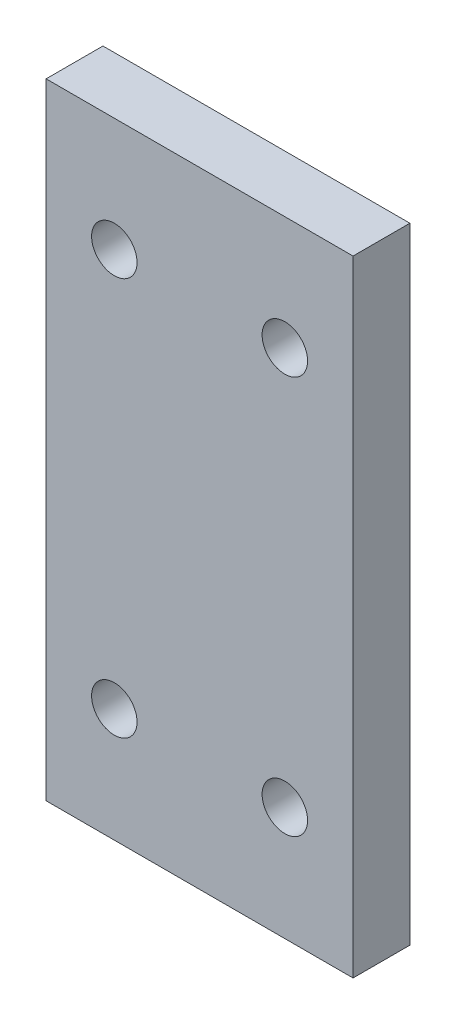
SolidWorks part; units mm, degrees
ref_plane "Front Plane" through (0, 0, 0) normal (0, 0, 1) x (1, 0, 0)
ref_plane "Top Plane" through (0, 0, 0) normal (0, 1, 0) x (1, 0, 0)
ref_plane "Right Plane" through (0, 0, 0) normal (1, 0, 0) x (0, 0, -1)
sketch "Sketch1" plane through (0, 0, 0) normal (0, 0, 1) x (1, 0, 0)
  line L0 (-25, 55) -> (-25, 0) construction
  line L1 (0, 0) -> (-27, 0)
  line L2 (0, 0) -> (0, 55)
  line L3 (0, 55) -> (-27, 55)
  line L4 (-27, 0) -> (-27, 55)
  line L5 (-13.5, 55) -> (-13.5, 61.6439) construction
  line L6 (-2, 55) -> (-2, 0) construction
  line L7 (-21, 45) -> (-21, 55) construction
  line L8 (-21, 10) -> (-21, 0) construction
  line L9 (-6, 10) -> (-6, 0) construction
  line L10 (-6, 45) -> (-6, 55) construction
  circle A0 centre (-21, 45) radius 2
  circle A1 centre (-21, 10) radius 2
  circle A2 centre (-6, 10) radius 2
  circle A3 centre (-6, 45) radius 2
  dimension "D3" = 4
  dimension "D4" = 4
  dimension "D5" = 4
  dimension "D6" = 4
  dimension "D8" = 35
  dimension "D1" = 55
  dimension "D2" = 27
  dimension "D7" = 2
extrude "Boss-Extrude1" add sketch "Sketch1" along normal blind 5
